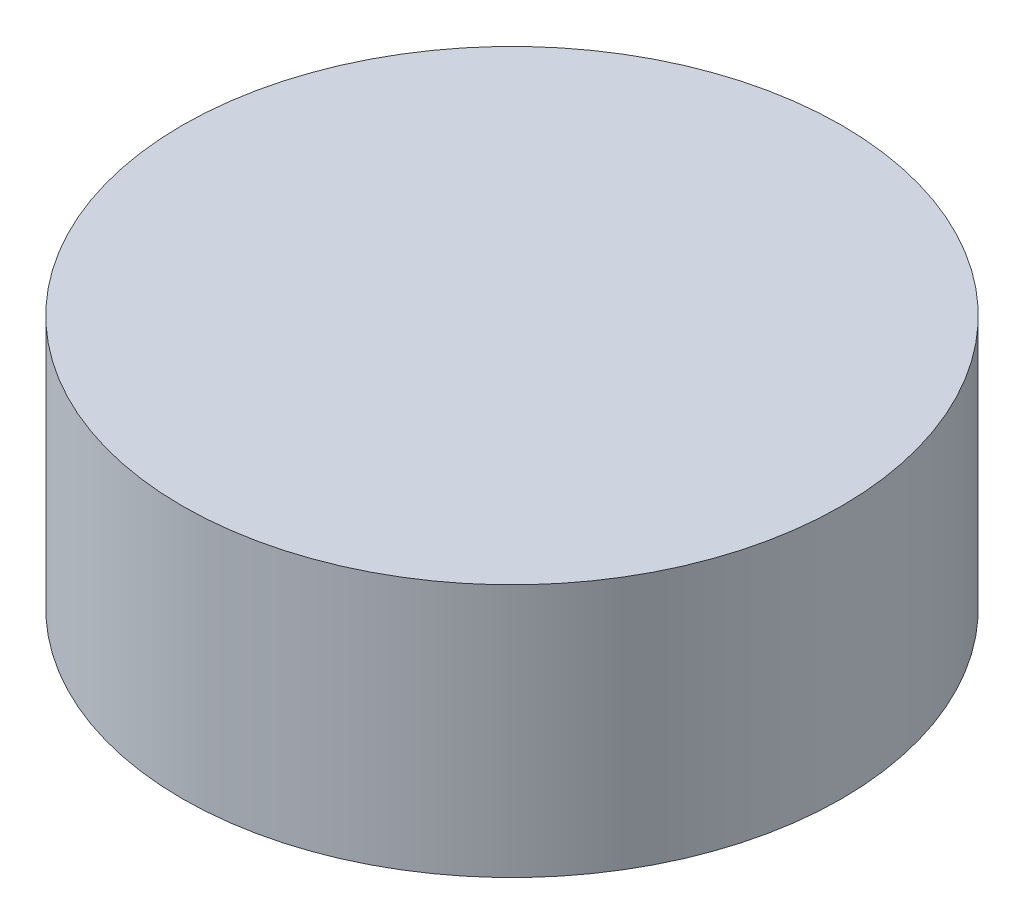
SolidWorks part; units mm, degrees
ref_plane "前基準面" through (0, 0, 0) normal (0, 0, 1) x (1, 0, 0)
ref_plane "上基準面" through (0, 0, 0) normal (0, 1, 0) x (1, 0, 0)
ref_plane "右基準面" through (0, 0, 0) normal (1, 0, 0) x (0, 0, -1)
sketch "草圖1" plane through (0, 0, 0) normal (0, 1, 0) x (1, 0, 0)
  circle A0 centre (0, 0) radius 32.25
extrude "填料-伸長1" add sketch "草圖1" along normal blind 24.8
